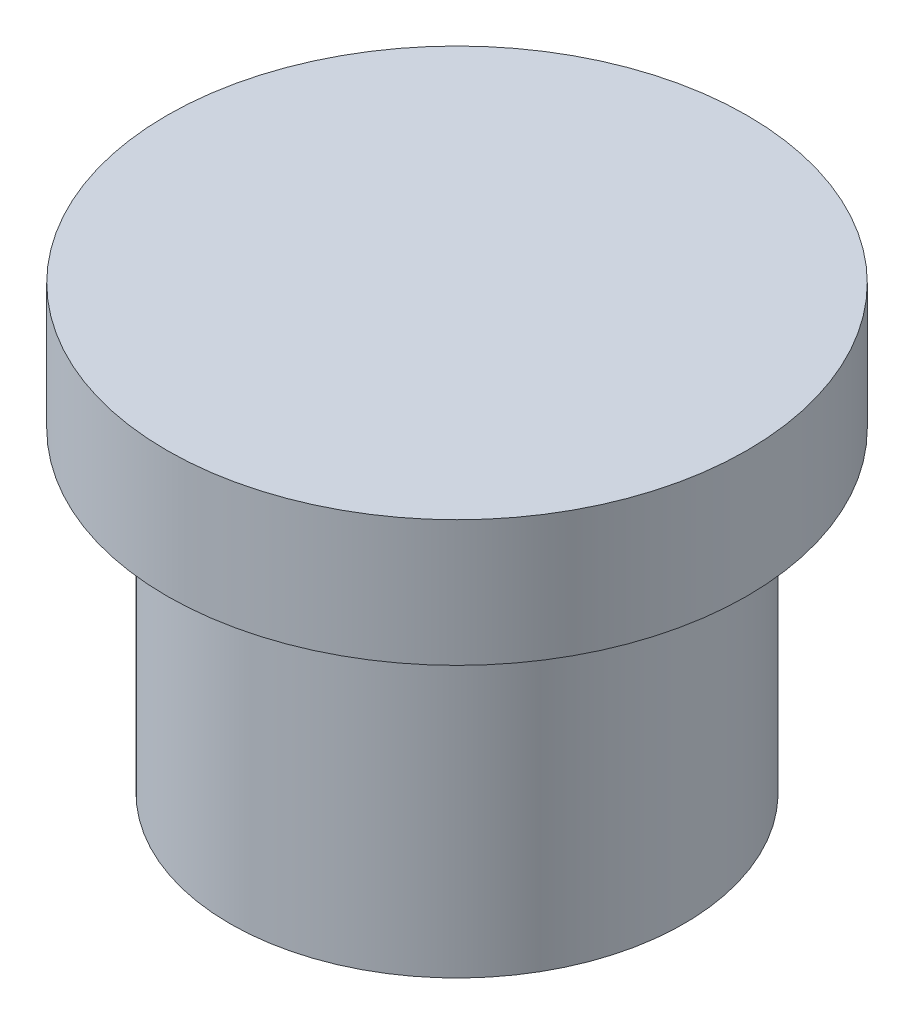
SolidWorks part; units mm, degrees
ref_plane "Front Plane" through (0, 0, 0) normal (0, 0, 1) x (1, 0, 0)
ref_plane "Top Plane" through (0, 0, 0) normal (0, 1, 0) x (1, 0, 0)
ref_plane "Right Plane" through (0, 0, 0) normal (1, 0, 0) x (0, 0, -1)
sketch "Sketch1" plane through (0, 0, 0) normal (0, 0, 1) x (1, 0, 0)
  line L0 (8.8083, 15.0604) -> (8.2444, 13.6704)
  line L1 (16.1374, -5) -> (18, -5)
  line L3 (0, 45) -> (18, 45)
  line L4 (18, -5) -> (18, 35)
  line L8 (18, 35) -> (23, 35)
  line L9 (23, 35) -> (23, 45)
  line L10 (23, 45) -> (18, 45)
  line L11 (0, 0) -> (0, 20.5141) construction
  line L13 (0, 45) -> (0, 35.9679)
  line L14 (0, 35.9679) -> (8.8083, 35.9679)
  line L15 (8.8083, 35.9679) -> (8.8083, 25.9679)
  line L16 (8.2444, 13.6704) -> (16.1374, -5)
  arc A0 (8.8083, 15.0604) -> (8.8083, 25.9679) centre (0, 20.5141) ccw
  dimension "D2" = 10.36
  dimension "D1" = 2.5
  dimension "D3" = 45
  dimension "D4" = 10
  dimension "D5" = 20.5141
  dimension "D6" = 1.5
  dimension "D8" = 50
  dimension "D9" = 18
  dimension "D12" = 5
  dimension "D11" = 10
  dimension "D7" = 5
  dimension "D10" = 9.0321
revolve "Revolve1" add sketch "Sketch1" angle 360 about L11
sketch "Sketch2" plane through (0, 0, 0) normal (1, 0, 0) x (0, 0, -1)
  line L0 (-18, 35) -> (-18, -5) construction
  line L1 (18, -5) -> (-18, -5)
  line L2 (18, -5) -> (18, 10)
  line L3 (18, 10) -> (-18, 10)
  line L4 (-18, -5) -> (-18, 10)
  dimension "D1" = 15
extrude "Cut-Extrude1" cut sketch "Sketch2" against normal through all both and the other way through all
equation "\"THREADRADIUS\"= 6mm"
equation "\"D2@Sketch1\"=(\"THREADRADIUS\"*1.3*1.2)+1mm"
